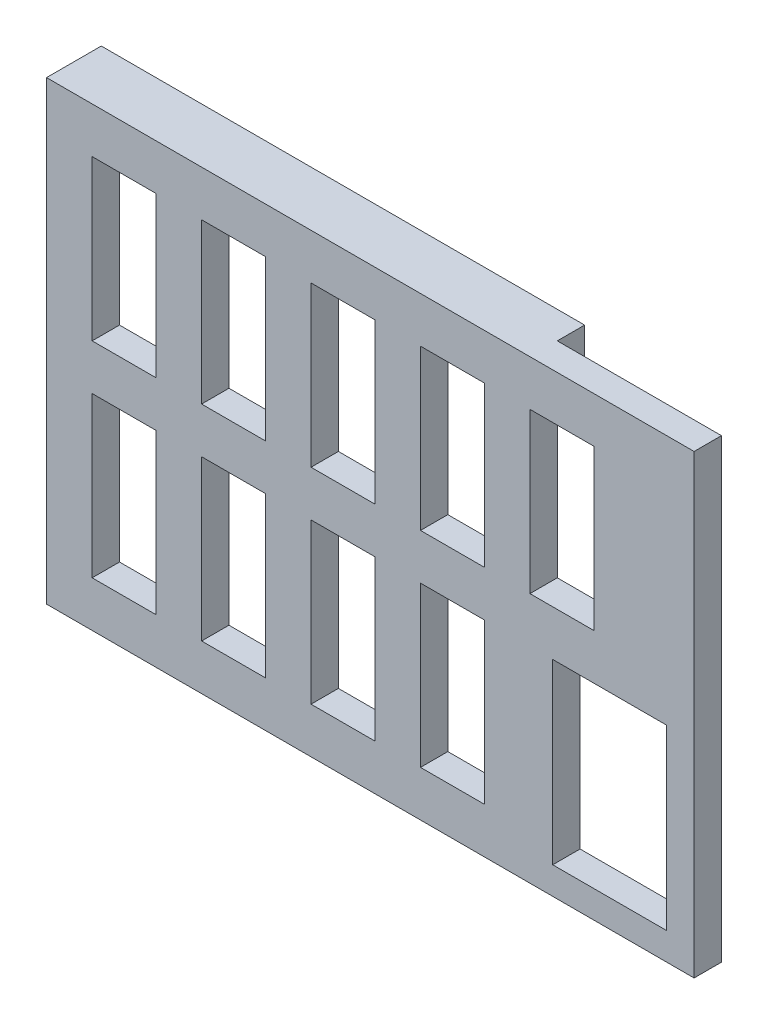
SolidWorks part; units mm, degrees
ref_plane "Front" through (0, 0, 0) normal (0, 0, 1) x (1, 0, 0)
ref_plane "Top" through (0, 0, 0) normal (0, 1, 0) x (1, 0, 0)
ref_plane "Right" through (0, 0, 0) normal (1, 0, 0) x (0, 0, -1)
sketch "Эскиз1" plane through (0, 0, 0) normal (0, 1, 0) x (1, 0, 0)
  line L0 (2.25, 0) -> (-2.25, 0)
  line L1 (-2.25, 0) -> (-4, 3)
  line L2 (-4, 3) -> (4, 3)
  line L3 (4, 3) -> (2.25, 0)
  line L4 (0, 0) -> (0, 8.6103) construction
  dimension "D1" = 8
  dimension "D2" = 3
  dimension "D3" = 4.5
extrude "Бобышка-Вытянуть1" add sketch "Эскиз1" along normal blind 5
sketch "Эскиз2" plane through (0, 5, 0) normal (0, 1, 0) x (1, 0, 0)
  line L0 (-26.5, 3) -> (26.5, 3)
  line L1 (26.5, 3) -> (26.5, 0)
  line L2 (26.5, 0) -> (-26.5, 0)
  line L3 (-26.5, 0) -> (-26.5, 3)
  line L4 (4, 3) -> (-4, 3) construction
  line L5 (-2.25, 0) -> (2.25, 0) construction
  line L6 (0, 0) -> (0, 3) construction
  dimension "D1" = 26.5
extrude "Бобышка-Вытянуть2" add sketch "Эскиз2" along normal blind 3
sketch "Эскиз3" plane through (0, 0, 0) normal (0, 0, 1) x (1, 0, 0)
  line L1 (-26.5, 8) -> (26.5, 8)
  line L2 (-26.5, 8) -> (-26.5, -42)
  line L3 (-26.5, -42) -> (26.5, -42)
  line L4 (26.5, 8) -> (26.5, -42)
  dimension "D1" = 50
extrude "Бобышка-Вытянуть3" add sketch "Эскиз3" along normal blind 3
sketch "Эскиз4" plane through (26.5, 0, 0) normal (1, 0, 0) x (0, 0, -1)
  line L0 (0, -42) -> (0, 5) construction
  line L1 (-3, 8) -> (0, 8)
  line L2 (-3, 8) -> (-3, -42)
  line L3 (-3, -42) -> (0, -42)
  line L4 (0, 8) -> (0, -42)
  dimension "D1" = 50
extrude "Бобышка-Вытянуть4" add sketch "Эскиз4" along normal blind 18
sketch "Эскиз5" plane through (0, 0, 3) normal (0, 0, 1) x (1, 0, 0)
  line L0 (44.5, 8) -> (-26.5, 8) construction
  line L1 (-21.5, 3) -> (-14.5, 3)
  line L2 (-21.5, 3) -> (-21.5, -14.5)
  line L3 (-21.5, -14.5) -> (-14.5, -14.5)
  line L4 (-14.5, 3) -> (-14.5, -14.5)
  line L5 (-21.5, -19.5) -> (-14.5, -19.5)
  line L6 (-21.5, -19.5) -> (-21.5, -37)
  line L7 (-21.5, -37) -> (-14.5, -37)
  line L8 (-14.5, -19.5) -> (-14.5, -37)
  line L9 (2.5, 3) -> (9.5, 3)
  line L10 (2.5, 3) -> (2.5, -14.5)
  line L11 (2.5, -14.5) -> (9.5, -14.5)
  line L12 (9.5, 3) -> (9.5, -14.5)
  line L13 (2.5, -19.5) -> (9.5, -19.5)
  line L14 (2.5, -19.5) -> (2.5, -37)
  line L15 (2.5, -37) -> (9.5, -37)
  line L16 (9.5, -19.5) -> (9.5, -37)
  line L17 (-9.5, 3) -> (-2.5, 3)
  line L18 (-9.5, 3) -> (-9.5, -14.5)
  line L19 (-9.5, -14.5) -> (-2.5, -14.5)
  line L20 (-2.5, 3) -> (-2.5, -14.5)
  line L21 (-9.5, -19.5) -> (-2.5, -19.5)
  line L22 (-9.5, -19.5) -> (-9.5, -37)
  line L23 (-9.5, -37) -> (-2.5, -37)
  line L24 (-2.5, -19.5) -> (-2.5, -37)
  line L25 (26.5, 3) -> (33.5, 3)
  line L26 (26.5, 3) -> (26.5, -14.5)
  line L27 (26.5, -14.5) -> (33.5, -14.5)
  line L28 (33.5, 3) -> (33.5, -14.5)
  line L29 (14.5, 3) -> (21.5, 3)
  line L30 (14.5, 3) -> (14.5, -14.5)
  line L31 (14.5, -14.5) -> (21.5, -14.5)
  line L32 (21.5, 3) -> (21.5, -14.5)
  line L33 (21.5, -19.5) -> (14.5, -19.5)
  line L34 (21.5, -19.5) -> (21.5, -37)
  line L35 (21.5, -37) -> (14.5, -37)
  line L36 (14.5, -19.5) -> (14.5, -37)
  line L37 (-26.5, 8) -> (-26.5, -42) construction
  line L38 (-26.5, -42) -> (44.5, -42) construction
  dimension "D1" = 5
  dimension "D2" = 5
  dimension "D3" = 5
  dimension "D4" = 5
  dimension "D5" = 5
  dimension "D6" = 5
  dimension "D7" = 5
  dimension "D8" = 5
  dimension "D9" = 7
extrude "Вырез-Вытянуть1" cut sketch "Эскиз5" against normal blind 3
sketch "Эскиз7" plane through (0, 0, 3) normal (0, 0, 1) x (1, 0, 0)
  line L0 (-26.5, -42) -> (44.5, -42) construction
  line L1 (29, -19.5) -> (41.5, -19.5)
  line L2 (29, -19.5) -> (29, -39)
  line L3 (29, -39) -> (41.5, -39)
  line L4 (41.5, -19.5) -> (41.5, -39)
  line L5 (44.5, 8) -> (44.5, -42) construction
  dimension "D1" = 12.5
  dimension "D2" = 19.5
  dimension "D3" = 3
  dimension "D4" = 3
extrude "Вырез-Вытянуть2" cut sketch "Эскиз7" against normal blind 3
